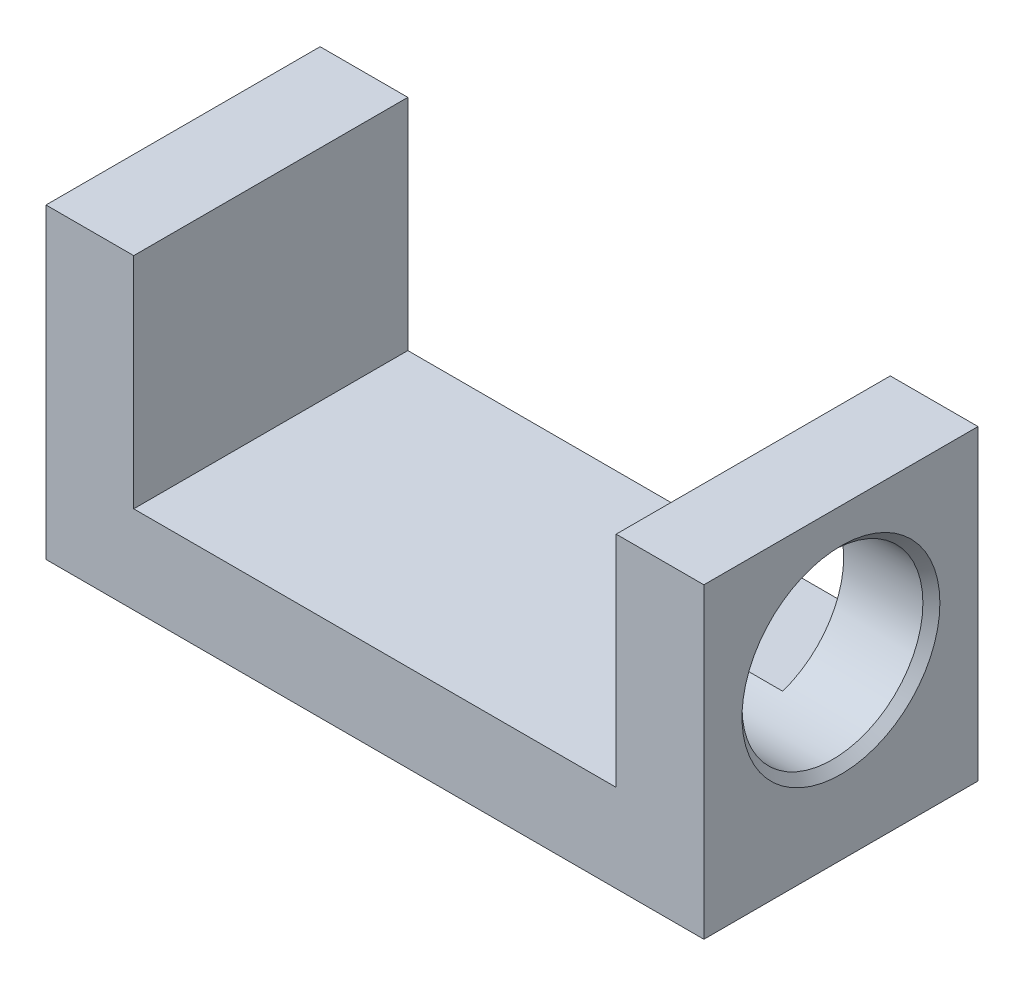
SolidWorks part; units mm, degrees
material "2024 Сплав"
ref_plane "Спереди" through (0, 0, 0) normal (0, 0, 1) x (1, 0, 0)
ref_plane "Сверху" through (0, 0, 0) normal (0, 1, 0) x (1, 0, 0)
ref_plane "Справа" through (0, 0, 0) normal (1, 0, 0) x (0, 0, -1)
sketch "Эскиз1" plane through (0, 0, 0) normal (0, 0, 1) x (1, 0, 0)
  line L0 (0, 0) -> (-117.6816, 0) construction
  line L1 (-60, 12.2) -> (0, 12.2)
  line L2 (-60, 12.2) -> (-60, -15.8)
  line L3 (-60, -15.8) -> (0, -15.8)
  line L4 (0, 12.2) -> (0, -15.8)
  line L5 (-52, 12.2) -> (-52, -7.8) construction
  line L6 (-52, -7.8) -> (-8, -7.8) construction
  line L7 (-8, -7.8) -> (-8, 12.2) construction
  dimension "D1" = 60
  dimension "D2" = 15.8
  dimension "D3" = 28
  dimension "D4" = 44
  dimension "D5" = 8
  dimension "D6" = 8
extrude "Бобышка-Вытянуть1" add sketch "Эскиз1" along normal mid plane 25
sketch "Эскиз2" plane through (0, 0, 0) normal (0, 0, 1) x (1, 0, 0)
  line L0 (-52, -7.8) -> (-8, -7.8) construction
  line L1 (-52, 12.2) -> (-52, -7.8) construction
  line L2 (-60, 12.2) -> (0, 12.2) construction
  line L3 (-8, -7.8) -> (-8, 12.2) construction
  line L4 (-52, -7.8) -> (-8, -7.8)
  line L5 (-52, 12.2) -> (-52, -7.8)
  line L6 (-52, 12.2) -> (-8, 12.2)
  line L7 (-8, -7.8) -> (-8, 12.2)
extrude "Вырез-Вытянуть1" cut sketch "Эскиз2" against normal through all and the other way through all
hole_wizard "Отверстие обработанное метчиком M18x1.51" positions "Эскиз3" profile "Эскиз4" tap size "M18x1.5" standard "ISO"
sketch "Эскиз3" plane through (0, 0, 0) normal (1, 0, 0) x (0, 0, -1)
  point P0 (0, 0)
sketch "Эскиз4" plane through (0, 0, 0) normal (0, 1, 0) x (0, 0, -1)
  line L0 (0, 0) -> (0, 17.9571)
  line L1 (0, 17.9571) -> (8.25, 13)
  line L2 (8.25, 13) -> (8.25, 0.775)
  line L3 (8.25, 0.775) -> (9.025, 0)
  line L5 (9.025, 0) -> (0, 0)
  line L6 (-8.25, 0.775) -> (-9.025, 0) construction
  line L10 (0, 17.9571) -> (-8.25, 13) construction
  line L11 (0, -6.35) -> (0, 107.95) construction
  dimension "Диаметр сверла" = 16.5
  dimension "Глубина сверла" = 13
  dimension "Диаметр передней зенковки" = 18.05
  dimension "Угол передней зенковки" = 90
  dimension "Угол заточки сверла" = 118
cosmetic thread "Отверстие резьбы1" parameters "D1"=8, "D2"=18
